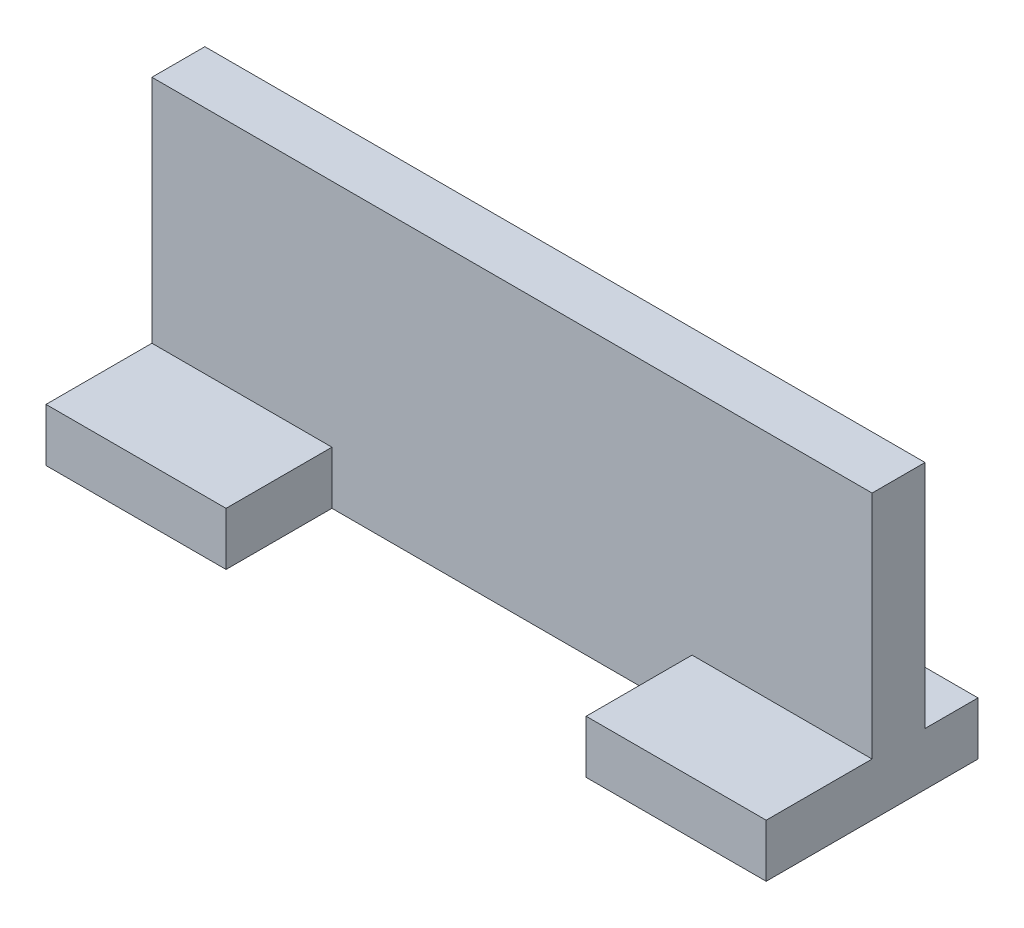
SolidWorks part; units mm, degrees
ref_plane "Front Plane" through (0, 0, 0) normal (0, 0, 1) x (1, 0, 0)
ref_plane "Top Plane" through (0, 0, 0) normal (0, 1, 0) x (1, 0, 0)
ref_plane "Right Plane" through (0, 0, 0) normal (1, 0, 0) x (0, 0, -1)
sketch "Sketch1" plane through (0, 0, 0) normal (0, 0, 1) x (1, 0, 0)
  line L1 (-68, 26.75) -> (68, 26.75)
  line L2 (-68, 26.75) -> (-68, -26.75)
  line L3 (-68, -26.75) -> (68, -26.75)
  line L4 (68, 26.75) -> (68, -26.75)
  line L5 (-68, 26.75) -> (68, -26.75) construction
  line L6 (-68, -26.75) -> (68, 26.75) construction
  point P0 (0, 0)
  dimension "D1" = 136
  dimension "D2" = 53.5
extrude "Boss-Extrude1" add sketch "Sketch1" along normal blind 10
sketch "Sketch2" plane through (0, 0, 0) normal (0, 0, -1) x (-1, 0, 0)
  line L0 (68, 26.75) -> (68, -26.75) construction
  line L1 (-68, 26.75) -> (68, 26.75) construction
  line L2 (0, 0) -> (0, 36.069) construction
  circle A0 centre (12.5, 9.25) radius 5
  circle A1 centre (-12.5, 9.25) radius 5
  dimension "D1" = 10
  dimension "D2" = 55.5
  dimension "D3" = 17.5
  dimension "D5" = 25
  dimension "D4" = 2
extrude "Boss-Extrude2" add sketch "Sketch2" along normal blind 12
sketch "Sketch3" plane through (-68, 0, 0) normal (-1, 0, 0) x (0, 0, 1)
  line L1 (0, -26.75) -> (-10, -26.75)
  line L2 (0, -26.75) -> (0, -16.75)
  line L3 (0, -16.75) -> (-10, -16.75)
  line L4 (-10, -26.75) -> (-10, -16.75)
  line L5 (10, -26.75) -> (30, -26.75)
  line L6 (10, -26.75) -> (10, -16.75)
  line L7 (10, -16.75) -> (30, -16.75)
  line L8 (30, -26.75) -> (30, -16.75)
  dimension "D1" = 20
  dimension "D2" = 10
  dimension "D3" = 10
  dimension "D4" = 10
ref_plane "Plane1" through (0, 0, 0) normal (-1, 0, 0) x (0, 0, 1)
extrude "Boss-Extrude3" add sketch "Sketch3" against normal blind 34
mirror "Mirror2" about plane through (0, 0, 0) normal (-1, 0, 0) of "Boss-Extrude3"
